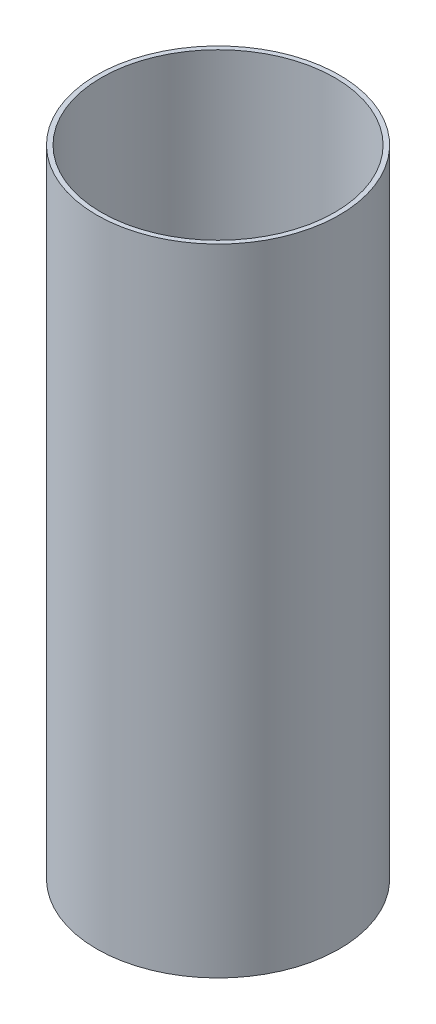
SolidWorks part; units mm, degrees
ref_plane "Спереди" through (0, 0, 0) normal (0, 0, 1) x (1, 0, 0)
ref_plane "Сверху" through (0, 0, 0) normal (0, 1, 0) x (1, 0, 0)
ref_plane "Справа" through (0, 0, 0) normal (1, 0, 0) x (0, 0, -1)
sketch "Эскиз1" plane through (0, 0, 0) normal (0, 1, 0) x (1, 0, 0)
  circle A0 centre (0, 0) radius 52.5
  circle A1 centre (0, 0) radius 50.5
  dimension "D1" = 105
  dimension "D2" = 2
extrude "Бобышка-Вытянуть1" add sketch "Эскиз1" along normal blind 275
